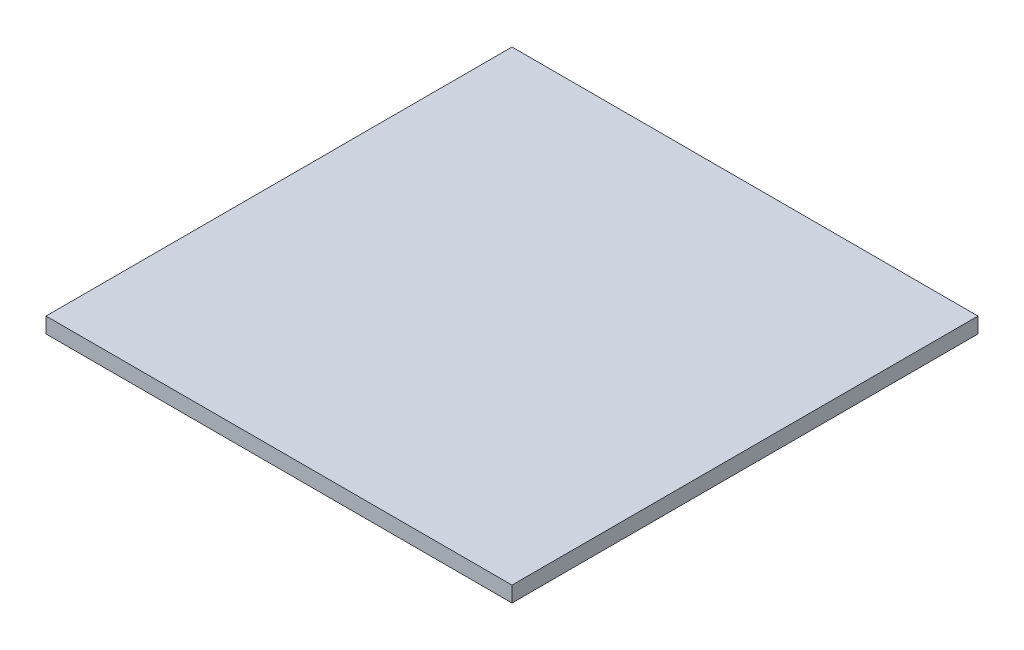
SolidWorks part; units mm, degrees
ref_plane "Plano frontal" through (0, 0, 0) normal (0, 0, 1) x (1, 0, 0)
ref_plane "Plano superior" through (0, 0, 0) normal (0, 1, 0) x (1, 0, 0)
ref_plane "Plano direito" through (0, 0, 0) normal (1, 0, 0) x (0, 0, -1)
sketch "Esboço1" plane through (0, 0, 0) normal (0, 1, 0) x (1, 0, 0)
  line L1 (-333.9393, 243.3639) -> (-183.9393, 243.3639)
  line L2 (-333.9393, 243.3639) -> (-333.9393, 93.3639)
  line L3 (-333.9393, 93.3639) -> (-183.9393, 93.3639)
  line L4 (-183.9393, 243.3639) -> (-183.9393, 93.3639)
  dimension "D1" = 150
  dimension "D2" = 150
extrude "Ressalto-extrusão1" add sketch "Esboço1" along normal blind 5
sketch "Esboço2" plane through (0, 0, 0) normal (0, -1, 0) x (-1, 0, 0)
  line L0 (333.9393, 93.3639) -> (183.9393, 93.3639) construction
  line L1 (333.9393, 243.3639) -> (333.9393, 93.3639) construction
  line L2 (183.9393, 93.3639) -> (183.9393, 243.3639) construction
  line L3 (183.9393, 243.3639) -> (333.9393, 243.3639) construction
  circle A0 centre (291.4393, 135.8639) radius 5
  circle A1 centre (226.4393, 135.8639) radius 5
  circle A2 centre (0, 0) radius 5
  circle A3 centre (226.4393, 200.8639) radius 5
  circle A4 centre (0, 0) radius 5
  circle A5 centre (291.4393, 200.8639) radius 5
  dimension "D1" = 10
  dimension "D2" = 42.5
  dimension "D3" = 42.5
  dimension "D4" = 10
  dimension "D5" = 10
  dimension "D6" = 42.5
  dimension "D7" = 42.5
  dimension "D8" = 10
  dimension "D9" = 10
  dimension "D10" = 42.5
  dimension "D11" = 42.5
  dimension "D12" = 10
  dimension "D13" = 10
  dimension "D14" = 42.5
  dimension "D15" = 42.5
extrude "Ressalto-extrusão2" add sketch "Esboço2" along normal blind 15 contours A0 | A1 | A5 | A3
sketch "Esboço4" plane through (0, -15, 0) normal (0, -1, 0) x (-1, 0, 0)
  circle A0 centre (291.4393, 135.8639) radius 1.5
  circle A2 centre (226.4393, 135.8639) radius 1.5
  circle A3 centre (291.4393, 200.8639) radius 1.5
  circle A4 centre (226.4393, 200.8639) radius 1.5
  dimension "D1" = 3
  dimension "D2" = 3
  dimension "D3" = 3
  dimension "D4" = 3
extrude "Corte-extrusão1" cut sketch "Esboço4" against normal blind 15
